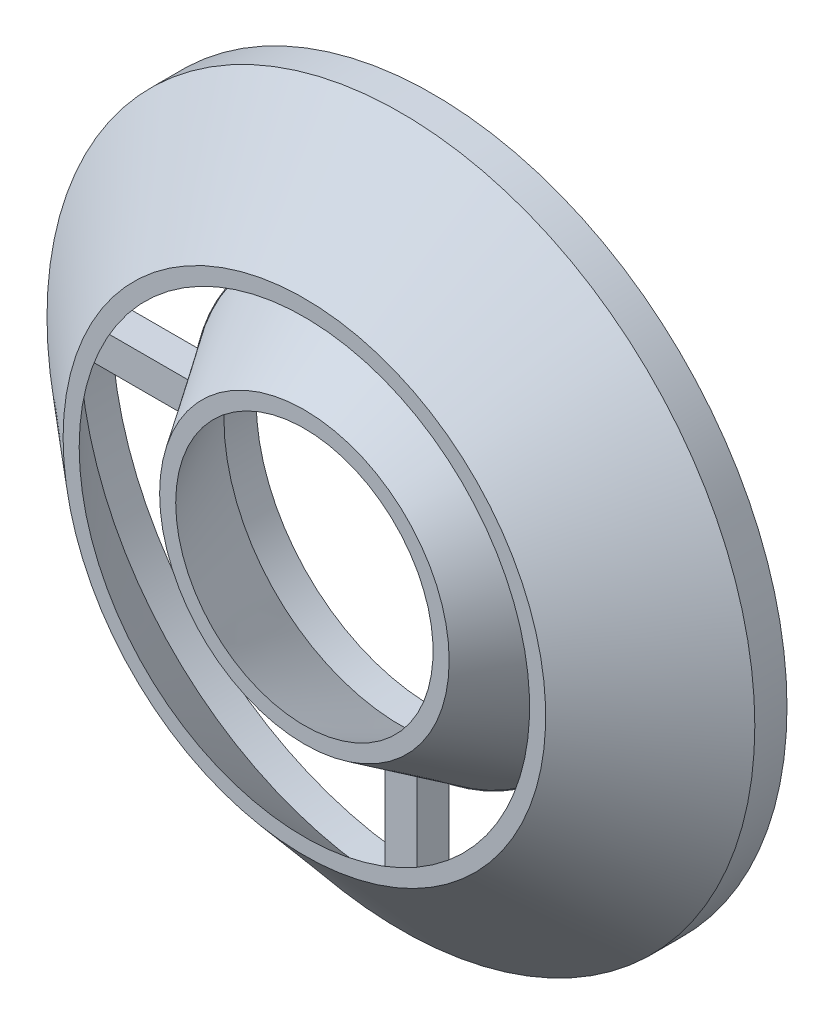
SolidWorks part; units mm, degrees
ref_plane "Спереди" through (0, 0, 0) normal (0, 0, 1) x (1, 0, 0)
ref_plane "Сверху" through (0, 0, 0) normal (0, 1, 0) x (1, 0, 0)
ref_plane "Справа" through (0, 0, 0) normal (1, 0, 0) x (0, 0, -1)
sketch "Эскиз2" plane through (0, 0, 0) normal (0, 0, 1) x (1, 0, 0)
  line L0 (0, 0) -> (0, 22) construction
  line L1 (19.975, -1) -> (12.9615, -1)
  line L2 (1, 19.975) -> (1, 12.9615)
  line L3 (19.975, 1) -> (12.9615, 1)
  line L4 (-1, 19.975) -> (-1, 12.9615)
  line L5 (1, 19.975) -> (-1, 12.9615) construction
  line L6 (1, 12.9615) -> (-1, 19.975) construction
  line L7 (-1, -19.975) -> (-1, -12.9615)
  line L8 (1, -19.975) -> (1, -12.9615)
  line L9 (-19.975, 1) -> (-12.9615, 1)
  line L10 (-19.975, -1) -> (-12.9615, -1)
  circle A0 centre (0, 0) radius 11
  circle A1 centre (0, 0) radius 13
  circle A2 centre (0, 0) radius 20
  circle A3 centre (0, 0) radius 22
  arc A4 (1, 12.9615) -> (-1, 12.9615) centre (0, 0) ccw
  point P6 (0, 16.4682)
  dimension "D1" = 22
  dimension "D2" = 2
  dimension "D3" = 40
  dimension "D4" = 2
  dimension "D5" = 2
  dimension "D6" = 4
extrude "Бобышка-Вытянуть1" add sketch "Эскиз2" along normal blind 2
ref_plane "Плоскость1" through (0, 0, 8) normal (0, 0, 1) x (1, 0, 0)
sketch "Эскиз3" plane through (0, 0, 8) normal (0, 0, 1) x (1, 0, 0)
  circle A0 centre (0, 0) radius 8
  circle A1 centre (0, 0) radius 9
  circle A2 centre (0, 0) radius 14
  circle A3 centre (0, 0) radius 15
  dimension "D1" = 16
  dimension "D2" = 1
  dimension "D3" = 5
  dimension "D4" = 1
sketch "Эскиз4" plane through (0, 0, 0) normal (0, 1, 0) x (1, 0, 0)
  line L2 (11, -2) -> (8, -8)
  line L3 (8, -8) -> (9, -8)
  line L4 (12.9615, -2) -> (9, -8)
  line L5 (14, -8) -> (19.975, -2)
  line L6 (14, -8) -> (15, -8)
  line L7 (15, -8) -> (22, -2)
  line L8 (11, -2) -> (12.9615, -2)
  line L9 (19.975, -2) -> (22, -2)
  point P0 (8, -8)
  dimension "D1" = 8
  dimension "D2" = 8
  dimension "D3" = 1
  dimension "D4" = 1
  dimension "D5" = 5
ref_axis "Ось1" through (0, 0, -0.4) along (0, 0, 1)
revolve "Повернуть1" add sketch "Эскиз4" angle 360 about axis through (0, 0, -0.4) along (0, 0, 1)
